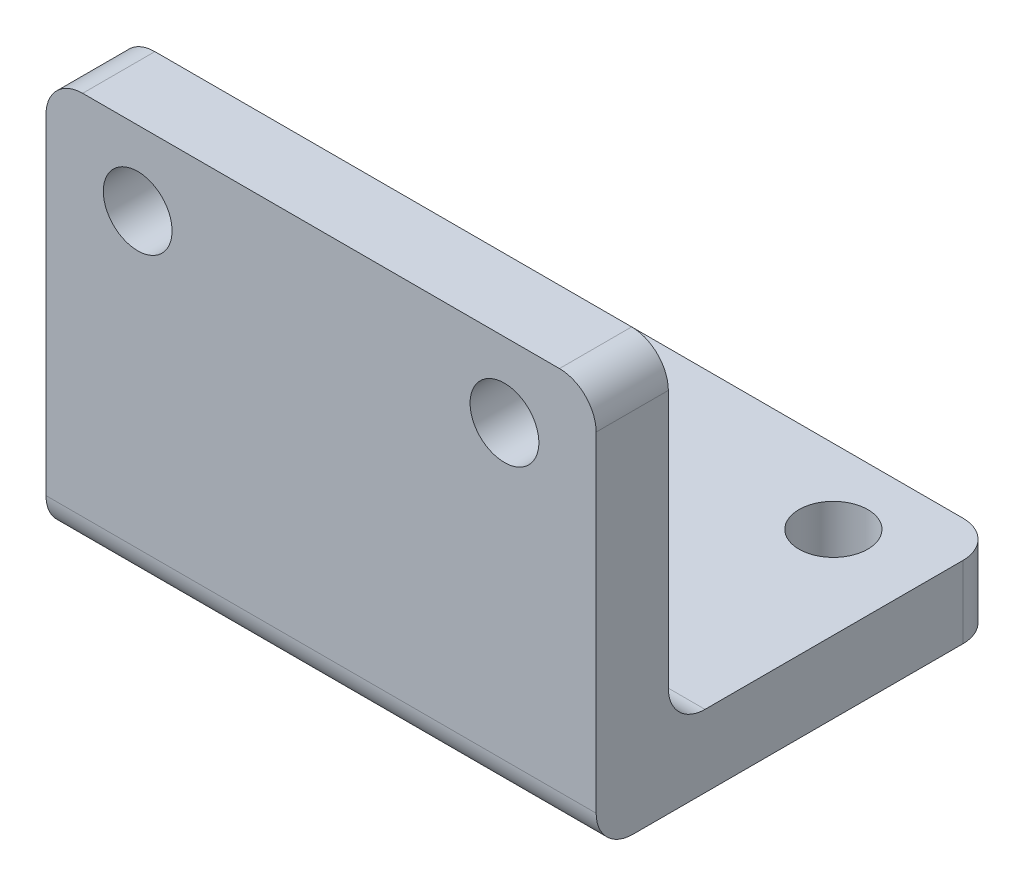
SolidWorks part; units mm, degrees
ref_plane "Front Plane" through (0, 0, 0) normal (0, 0, 1) x (1, 0, 0)
ref_plane "Top Plane" through (0, 0, 0) normal (0, 1, 0) x (1, 0, 0)
ref_plane "Right Plane" through (0, 0, 0) normal (1, 0, 0) x (0, 0, -1)
sketch "Sketch2" plane through (0, 0, 0) normal (1, 0, 0) x (0, 0, -1)
  line L0 (0, 0) -> (27.94, 0)
  line L2 (0, 0) -> (0, 27.94)
  line L3 (0, 27.94) -> (5, 27.94)
  line L4 (5, 5) -> (5, 27.94)
  line L7 (5, 5) -> (27.94, 5)
  line L8 (27.94, 0) -> (27.94, 5)
  point P0 (37.0335, -0.6791)
  dimension "D1" = 27.94
  dimension "D2" = 27.94
  dimension "D3" = 5
  dimension "D4" = 5
extrude "Boss-Extrude1" add sketch "Sketch2" along normal blind 38.1
fillet "Fillet1" radius 2.54 6 edges at (38.1, 2.5, -27.94) (0, 2.5, -27.94) (0, 27.94, -2.5) (38.1, 27.94, -2.5) (19.05, 5, -5) (19.05, 0, 0)
sketch "Sketch3" plane through (0, 0, -5) normal (0, 0, -1) x (-1, 0, 0)
  line L0 (-38.1, 7.54) -> (0, 7.54) construction
  line L1 (-31.75, 7.54) -> (-6.35, 7.54) construction
  line L2 (-31.75, 7.54) -> (-31.75, 22.78) construction
  line L3 (-31.75, 22.78) -> (-6.35, 22.78) construction
  line L4 (-6.35, 7.54) -> (-6.35, 22.78) construction
  line L5 (-19.05, 27.94) -> (-19.05, 22.78) construction
  line L6 (-35.56, 27.94) -> (-2.54, 27.94) construction
  circle A0 centre (-31.75, 22.78) radius 2.3813
  circle A1 centre (-6.35, 22.78) radius 2.3813
  point P12 (0, 0)
  point P13 (0, 0)
  dimension "D1" = 4.7625
  dimension "D2" = 15.24
  dimension "D3" = 25.4
extrude "guess_of_where_holes_are" cut sketch "Sketch3" against normal through all
sketch "Sketch4" plane through (0, 5, 0) normal (0, 1, 0) x (1, 0, 0)
  line L0 (0, 7.54) -> (38.1, 7.54) construction
  line L1 (31.75, 7.54) -> (6.35, 7.54) construction
  line L2 (31.75, 7.54) -> (31.75, 22.78) construction
  line L3 (31.75, 22.78) -> (6.35, 22.78) construction
  line L4 (6.35, 7.54) -> (6.35, 22.78) construction
  circle A0 centre (31.75, 22.78) radius 2.3812
  circle A1 centre (6.35, 22.78) radius 2.3813
  dimension "D2" = 4.7625
  dimension "D1" = 15.24
extrude "Cut-Extrude2" cut sketch "Sketch4" against normal through all
